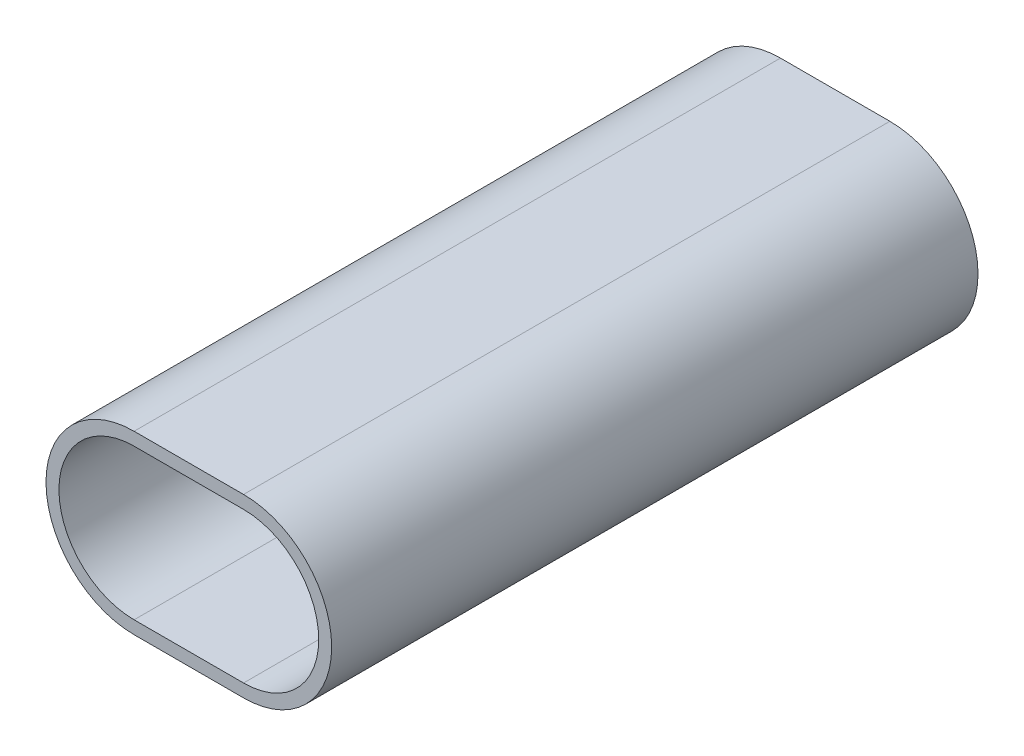
SolidWorks part; units mm, degrees
ref_plane "Front Plane" through (0, 0, 0) normal (0, 0, 1) x (1, 0, 0)
ref_plane "Top Plane" through (0, 0, 0) normal (0, 1, 0) x (1, 0, 0)
ref_plane "Right Plane" through (0, 0, 0) normal (1, 0, 0) x (0, 0, -1)
sketch "Sketch2" plane through (0, 0, 0) normal (0, 0, 1) x (1, 0, 0)
  line L0 (-12.7, 0) -> (12.7, 0) construction
  line L1 (-12.7, 20.447) -> (12.7, 20.447)
  line L2 (-12.7, -20.447) -> (12.7, -20.447)
  line L3 (-12.7, 17.447) -> (12.7, 17.447)
  line L4 (-12.7, -17.447) -> (12.7, -17.447)
  arc A0 (-12.7, 20.447) -> (-12.7, -20.447) centre (-12.7, 0) ccw
  arc A1 (12.7, -20.447) -> (12.7, 20.447) centre (12.7, 0) ccw
  arc A2 (12.7, -17.447) -> (12.7, 17.447) centre (12.7, 0) ccw
  arc A3 (-12.7, 17.447) -> (-12.7, -17.447) centre (-12.7, 0) ccw
  point P3 (0, 0)
  point P8 (0, 0)
  dimension "D1" = 25.4
  dimension "D3" = 3
  dimension "D2" = 40.894
extrude "Boss-Extrude1" add sketch "Sketch2" along normal mid plane 150
